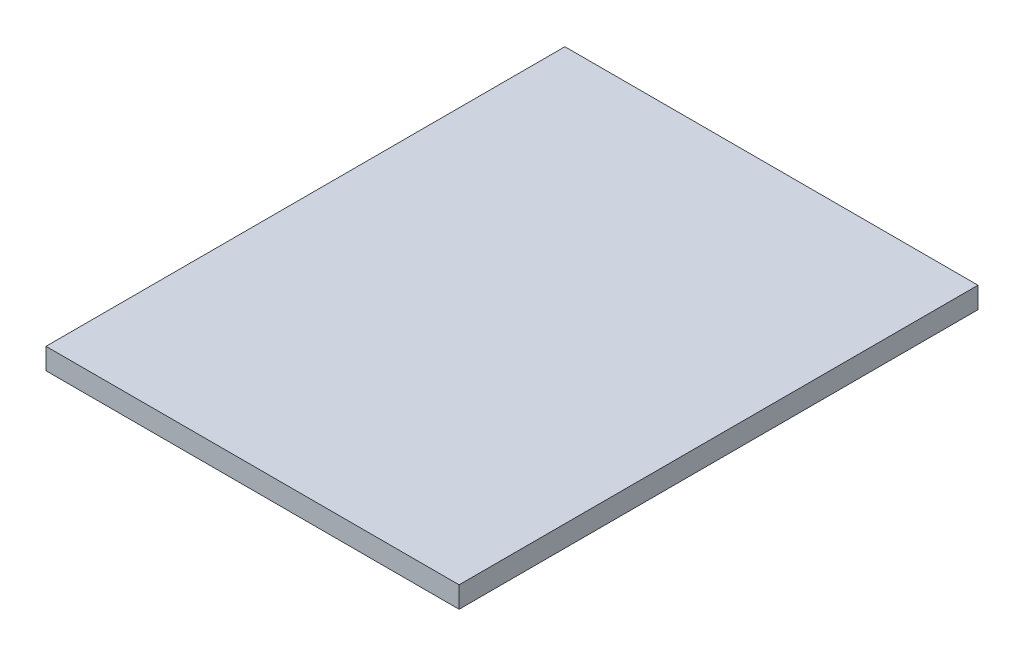
SolidWorks part; units mm, degrees
ref_plane "Alzado" through (0, 0, 0) normal (0, 0, 1) x (1, 0, 0)
ref_plane "Planta" through (0, 0, 0) normal (0, 1, 0) x (1, 0, 0)
ref_plane "Vista lateral" through (0, 0, 0) normal (1, 0, 0) x (0, 0, -1)
sketch "Croquis1" plane through (0, 0, 0) normal (0, 1, 0) x (1, 0, 0)
  line L1 (-134.7379, 163.4167) -> (235.2621, 163.4167)
  line L2 (-134.7379, 163.4167) -> (-134.7379, -301.3633)
  line L3 (-134.7379, -301.3633) -> (235.2621, -301.3633)
  line L4 (235.2621, 163.4167) -> (235.2621, -301.3633)
  dimension "D1" = 370
  dimension "D2" = 464.78
extrude "Saliente-Extruir1" add sketch "Croquis1" along normal blind 19
